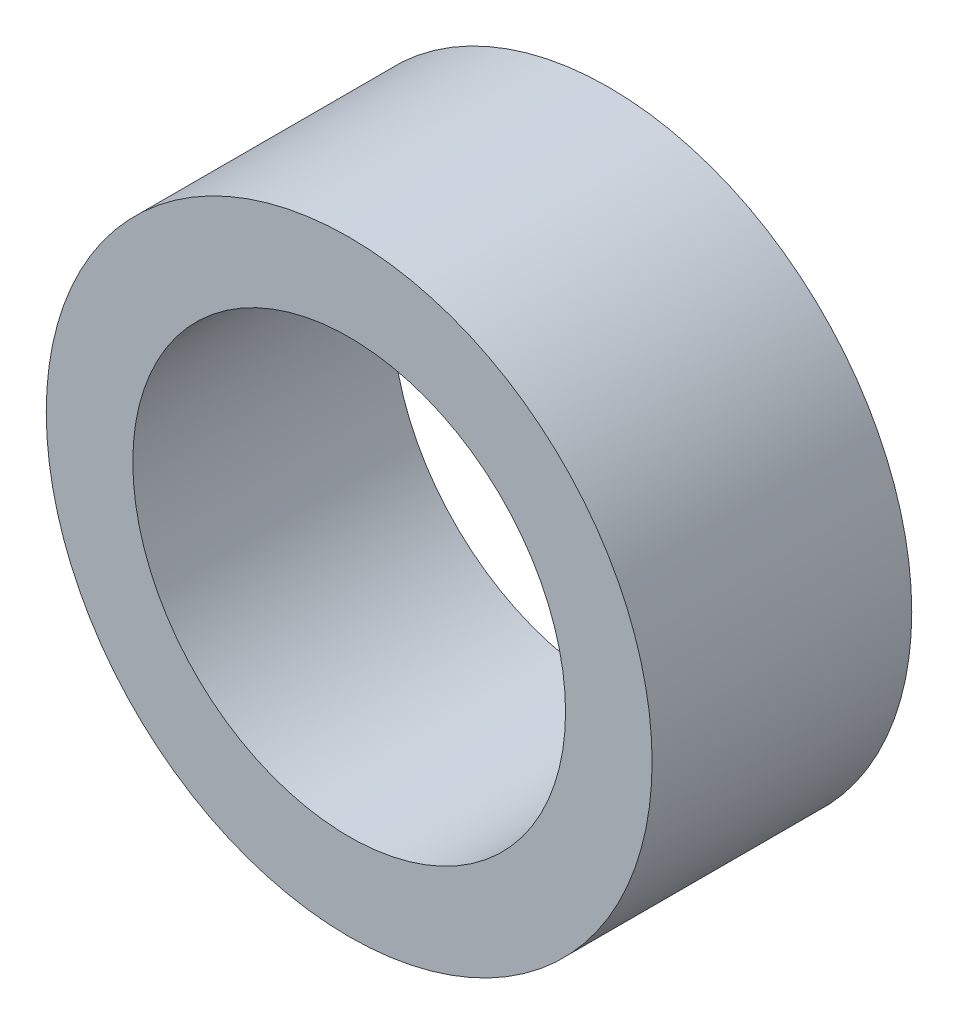
SolidWorks part; units mm, degrees
material "合金钢"
ref_plane "前视基准面" through (0, 0, 0) normal (0, 0, 1) x (1, 0, 0)
ref_plane "上视基准面" through (0, 0, 0) normal (0, 1, 0) x (1, 0, 0)
ref_plane "右视基准面" through (0, 0, 0) normal (1, 0, 0) x (0, 0, -1)
other "Configuration Table"
sketch "草图1" plane through (0, 0, 0) normal (0, 0, 1) x (1, 0, 0)
  line L0 (-13.6576, 0) -> (3.201, 0) construction
  line L1 (0, 5.8551) -> (0, -4.7348) construction
  circle A0 centre (0, 0) radius 2.5
  circle A1 centre (0, 0) radius 3.5
  dimension "D1" = 5
  dimension "D2" = 7
extrude "凸台-拉伸1" add sketch "草图1" along normal blind 3
